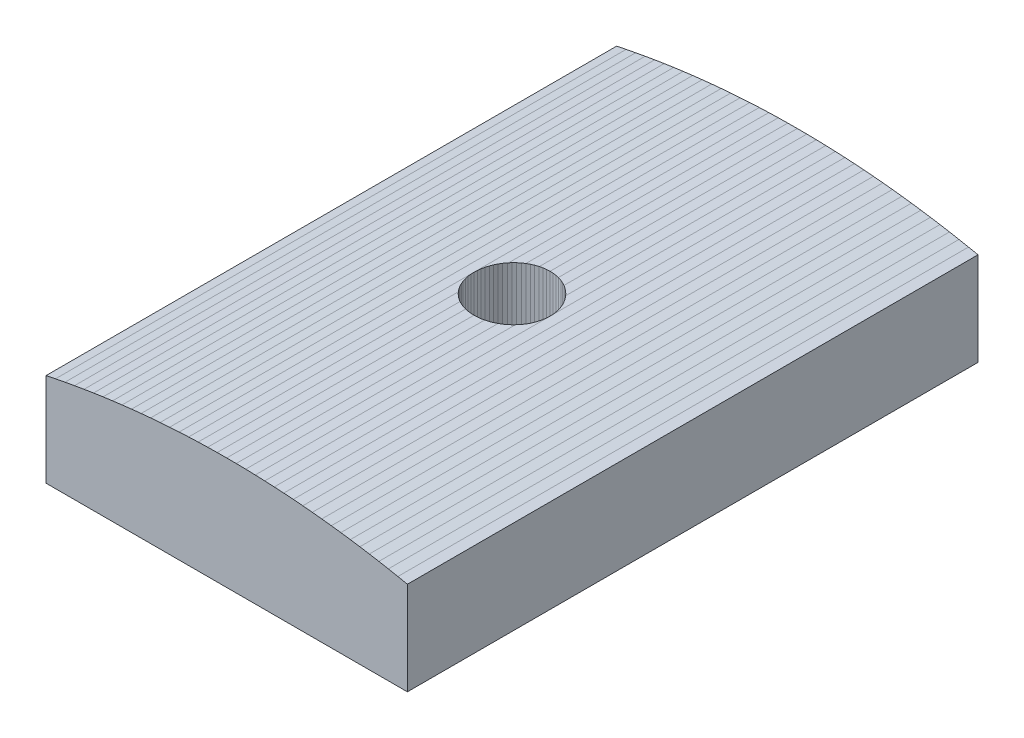
SolidWorks part; units mm, degrees
ref_plane "前视基准面" through (0, 0, 0) normal (0, 0, 1) x (1, 0, 0)
ref_plane "上视基准面" through (0, 0, 0) normal (0, 1, 0) x (1, 0, 0)
ref_plane "右视基准面" through (0, 0, 0) normal (1, 0, 0) x (0, 0, -1)
other "Configuration Table"
sketch "草图1" plane through (0, 0, 0) normal (0, 0, 1) x (1, 0, 0)
  line L0 (-190, 96) -> (190, 96)
  line L1 (190, 96) -> (190, 194)
  line L2 (190, 194) -> (180, 196.0499)
  line L3 (180, 196.0499) -> (170, 197.9889)
  line L4 (170, 197.9889) -> (160, 199.8172)
  line L5 (160, 199.8172) -> (150, 201.5346)
  line L6 (150, 201.5346) -> (140, 203.1413)
  line L7 (140, 203.1413) -> (130, 204.6371)
  line L8 (130, 204.6371) -> (120, 206.0222)
  line L9 (120, 206.0222) -> (110, 207.2964)
  line L10 (110, 207.2964) -> (100, 208.4598)
  line L11 (100, 208.4598) -> (90, 209.5125)
  line L12 (90, 209.5125) -> (80, 210.4543)
  line L13 (80, 210.4543) -> (70, 211.2853)
  line L14 (70, 211.2853) -> (60, 212.0055)
  line L15 (60, 212.0055) -> (50, 212.615)
  line L16 (50, 212.615) -> (40, 213.1136)
  line L17 (40, 213.1136) -> (30, 213.5014)
  line L18 (30, 213.5014) -> (20, 213.7784)
  line L19 (20, 213.7784) -> (10, 213.9446)
  line L20 (10, 213.9446) -> (0, 214)
  line L21 (0, 214) -> (-10, 213.9446)
  line L22 (-10, 213.9446) -> (-20, 213.7784)
  line L23 (-20, 213.7784) -> (-30, 213.5014)
  line L24 (-30, 213.5014) -> (-40, 213.1136)
  line L25 (-40, 213.1136) -> (-50, 212.615)
  line L26 (-50, 212.615) -> (-60, 212.0055)
  line L27 (-60, 212.0055) -> (-70, 211.2853)
  line L28 (-70, 211.2853) -> (-80, 210.4543)
  line L29 (-80, 210.4543) -> (-90, 209.5125)
  line L30 (-90, 209.5125) -> (-100, 208.4598)
  line L31 (-100, 208.4598) -> (-110, 207.2964)
  line L32 (-110, 207.2964) -> (-120, 206.0222)
  line L33 (-120, 206.0222) -> (-130, 204.6371)
  line L34 (-130, 204.6371) -> (-140, 203.1413)
  line L35 (-140, 203.1413) -> (-150, 201.5346)
  line L36 (-150, 201.5346) -> (-160, 199.8172)
  line L37 (-160, 199.8172) -> (-170, 197.9889)
  line L38 (-170, 197.9889) -> (-180, 196.0499)
  line L39 (-180, 196.0499) -> (-190, 194)
  line L40 (-190, 194) -> (-190, 96)
  dimension "x0" = 190
  dimension "x1" = 190
  dimension "x3" = 180
  dimension "x4" = 170
  dimension "x5" = 160
  dimension "x6" = 150
  dimension "x7" = 140
  dimension "x8" = 130
  dimension "x9" = 120
  dimension "x10" = 110
  dimension "x11" = 100
  dimension "x12" = 90
  dimension "x13" = 80
  dimension "x14" = 70
  dimension "x15" = 60
  dimension "x16" = 50
  dimension "x17" = 40
  dimension "x18" = 30
  dimension "x19" = 20
  dimension "x20" = 10
  dimension "x22" = 10
  dimension "x23" = 20
  dimension "x24" = 30
  dimension "x25" = 40
  dimension "x26" = 50
  dimension "x27" = 60
  dimension "x28" = 70
  dimension "x29" = 80
  dimension "x30" = 90
  dimension "x31" = 100
  dimension "x32" = 110
  dimension "x33" = 120
  dimension "x34" = 130
  dimension "x35" = 140
  dimension "x36" = 150
  dimension "x37" = 160
  dimension "x38" = 170
  dimension "x39" = 180
  dimension "y0" = 96
  dimension "y2" = 194
  dimension "y3" = 196.0499
  dimension "y4" = 197.9889
  dimension "y5" = 199.8172
  dimension "y6" = 201.5346
  dimension "y7" = 203.1413
  dimension "y8" = 204.6371
  dimension "y9" = 206.0222
  dimension "y10" = 207.2964
  dimension "y11" = 208.4598
  dimension "y12" = 209.5125
  dimension "y13" = 210.4543
  dimension "y14" = 211.2853
  dimension "y15" = 212.0055
  dimension "y16" = 212.615
  dimension "y17" = 213.1136
  dimension "y18" = 213.5014
  dimension "y19" = 213.7784
  dimension "y20" = 213.9446
  dimension "y21" = 214
  dimension "y22" = 213.9446
  dimension "y23" = 213.7784
  dimension "y24" = 213.5014
  dimension "y25" = 213.1136
  dimension "y26" = 212.615
  dimension "y27" = 212.0055
  dimension "y28" = 211.2853
  dimension "y29" = 210.4543
  dimension "y30" = 209.5125
  dimension "y31" = 208.4598
  dimension "y32" = 207.2964
  dimension "y33" = 206.0222
  dimension "y34" = 204.6371
  dimension "y35" = 203.1413
  dimension "y36" = 201.5346
  dimension "y37" = 199.8172
  dimension "y38" = 197.9889
  dimension "y39" = 196.0499
  dimension "y40" = 194
extrude "Arched_float" add sketch "草图1" along normal blind 600
sketch "草图2" plane through (0, 0, 0) normal (0, 1, 0) x (1, 0, 0)
  line L0 (40, -300) -> (39.8478, -303.4862)
  line L1 (39.8478, -303.4862) -> (39.3923, -306.9459)
  line L2 (39.3923, -306.9459) -> (38.637, -310.3528)
  line L3 (38.637, -310.3528) -> (37.5877, -313.6808)
  line L4 (37.5877, -313.6808) -> (36.2523, -316.9047)
  line L5 (36.2523, -316.9047) -> (34.641, -320)
  line L6 (34.641, -320) -> (32.7661, -322.9431)
  line L7 (32.7661, -322.9431) -> (30.6418, -325.7115)
  line L8 (30.6418, -325.7115) -> (28.2843, -328.2843)
  line L9 (28.2843, -328.2843) -> (25.7115, -330.6418)
  line L10 (25.7115, -330.6418) -> (22.9431, -332.7661)
  line L11 (22.9431, -332.7661) -> (20, -334.641)
  line L12 (20, -334.641) -> (16.9047, -336.2523)
  line L13 (16.9047, -336.2523) -> (13.6808, -337.5877)
  line L14 (13.6808, -337.5877) -> (10.3528, -338.637)
  line L15 (10.3528, -338.637) -> (6.9459, -339.3923)
  line L16 (6.9459, -339.3923) -> (3.4862, -339.8478)
  line L17 (3.4862, -339.8478) -> (0, -340)
  line L18 (0, -340) -> (-3.4862, -339.8478)
  line L19 (-3.4862, -339.8478) -> (-6.9459, -339.3923)
  line L20 (-6.9459, -339.3923) -> (-10.3528, -338.637)
  line L21 (-10.3528, -338.637) -> (-13.6808, -337.5877)
  line L22 (-13.6808, -337.5877) -> (-16.9047, -336.2523)
  line L23 (-16.9047, -336.2523) -> (-20, -334.641)
  line L24 (-20, -334.641) -> (-22.9431, -332.7661)
  line L25 (-22.9431, -332.7661) -> (-25.7115, -330.6418)
  line L26 (-25.7115, -330.6418) -> (-28.2843, -328.2843)
  line L27 (-28.2843, -328.2843) -> (-30.6418, -325.7115)
  line L28 (-30.6418, -325.7115) -> (-32.7661, -322.9431)
  line L29 (-32.7661, -322.9431) -> (-34.641, -320)
  line L30 (-34.641, -320) -> (-36.2523, -316.9047)
  line L31 (-36.2523, -316.9047) -> (-37.5877, -313.6808)
  line L32 (-37.5877, -313.6808) -> (-38.637, -310.3528)
  line L33 (-38.637, -310.3528) -> (-39.3923, -306.9459)
  line L34 (-39.3923, -306.9459) -> (-39.8478, -303.4862)
  line L35 (-39.8478, -303.4862) -> (-40, -300)
  line L36 (-40, -300) -> (-39.8478, -296.5138)
  line L37 (-39.8478, -296.5138) -> (-39.3923, -293.0541)
  line L38 (-39.3923, -293.0541) -> (-38.637, -289.6472)
  line L39 (-38.637, -289.6472) -> (-37.5877, -286.3192)
  line L40 (-37.5877, -286.3192) -> (-36.2523, -283.0953)
  line L41 (-36.2523, -283.0953) -> (-34.641, -280)
  line L42 (-34.641, -280) -> (-32.7661, -277.0569)
  line L43 (-32.7661, -277.0569) -> (-30.6418, -274.2885)
  line L44 (-30.6418, -274.2885) -> (-28.2843, -271.7157)
  line L45 (-28.2843, -271.7157) -> (-25.7115, -269.3582)
  line L46 (-25.7115, -269.3582) -> (-22.9431, -267.2339)
  line L47 (-22.9431, -267.2339) -> (-20, -265.359)
  line L48 (-20, -265.359) -> (-16.9047, -263.7477)
  line L49 (-16.9047, -263.7477) -> (-13.6808, -262.4123)
  line L50 (-13.6808, -262.4123) -> (-10.3528, -261.363)
  line L51 (-10.3528, -261.363) -> (-6.9459, -260.6077)
  line L52 (-6.9459, -260.6077) -> (-3.4862, -260.1522)
  line L53 (-3.4862, -260.1522) -> (0, -260)
  line L54 (0, -260) -> (3.4862, -260.1522)
  line L55 (3.4862, -260.1522) -> (6.9459, -260.6077)
  line L56 (6.9459, -260.6077) -> (10.3528, -261.363)
  line L57 (10.3528, -261.363) -> (13.6808, -262.4123)
  line L58 (13.6808, -262.4123) -> (16.9047, -263.7477)
  line L59 (16.9047, -263.7477) -> (20, -265.359)
  line L60 (20, -265.359) -> (22.9431, -267.2339)
  line L61 (22.9431, -267.2339) -> (25.7115, -269.3582)
  line L62 (25.7115, -269.3582) -> (28.2843, -271.7157)
  line L63 (28.2843, -271.7157) -> (30.6418, -274.2885)
  line L64 (30.6418, -274.2885) -> (32.7661, -277.0569)
  line L65 (32.7661, -277.0569) -> (34.641, -280)
  line L66 (34.641, -280) -> (36.2523, -283.0953)
  line L67 (36.2523, -283.0953) -> (37.5877, -286.3192)
  line L68 (37.5877, -286.3192) -> (38.637, -289.6472)
  line L69 (38.637, -289.6472) -> (39.3923, -293.0541)
  line L70 (39.3923, -293.0541) -> (39.8478, -296.5138)
  line L71 (39.8478, -296.5138) -> (40, -300)
extrude "Tether_pass_through" cut sketch "草图2" against normal through all and the other way through all
